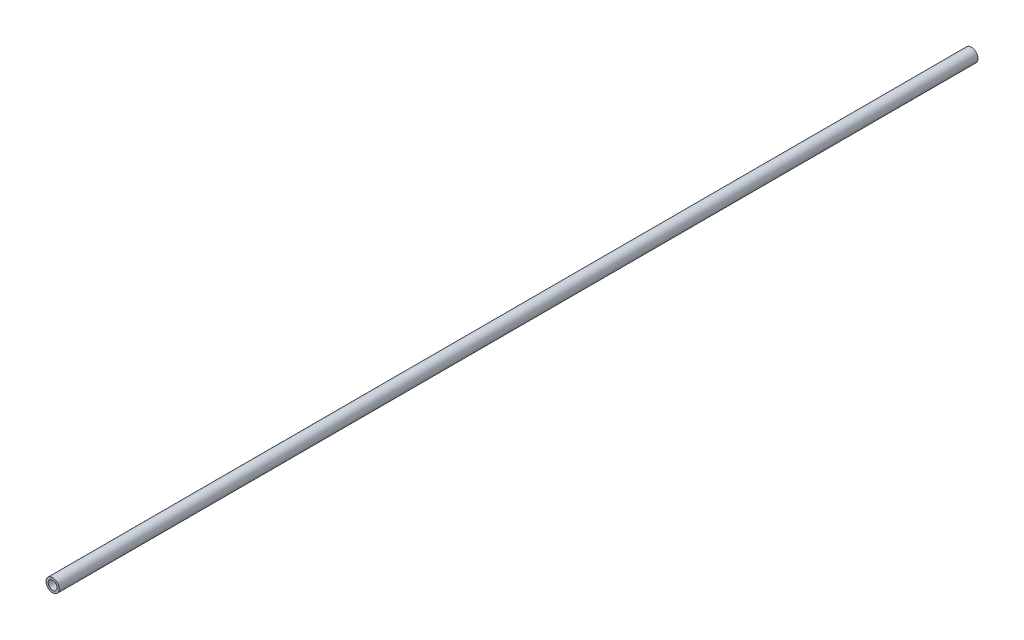
SolidWorks part; units mm, degrees
material "Hexcel AS4C (3000 Filaments)"
ref_plane "Front Plane" through (0, 0, 0) normal (0, 0, 1) x (1, 0, 0)
ref_plane "Top Plane" through (0, 0, 0) normal (0, 1, 0) x (1, 0, 0)
ref_plane "Right Plane" through (0, 0, 0) normal (1, 0, 0) x (0, 0, -1)
sketch "Sketch1" plane through (0, 0, 0) normal (0, 0, 1) x (1, 0, 0)
  circle A0 centre (0, 0) radius 3
extrude "Boss-Extrude1" add sketch "Sketch1" along normal blind 417.5
sketch "Sketch2" plane through (0, 0, 0) normal (0, 0, 1) x (1, 0, 0)
  circle A0 centre (0, 0) radius 2
extrude "Cut-Extrude1" cut sketch "Sketch2" along normal through all
